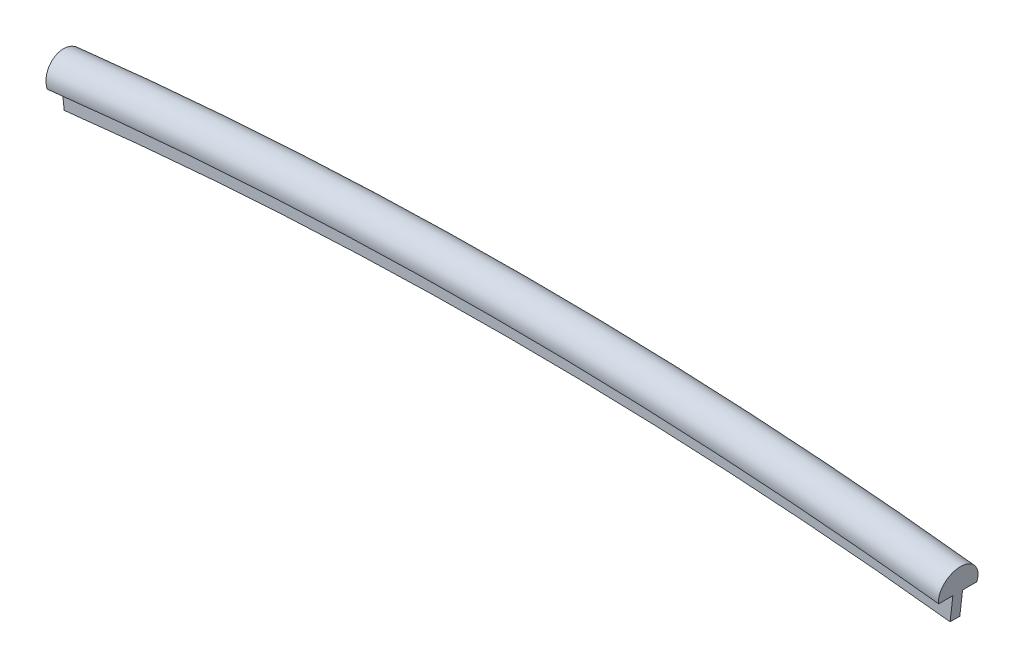
SolidWorks part; units mm, degrees
ref_plane "Front Plane" through (0, 0, 0) normal (0, 0, 1) x (1, 0, 0)
ref_plane "Top Plane" through (0, 0, 0) normal (0, 1, 0) x (1, 0, 0)
ref_plane "Right Plane" through (0, 0, 0) normal (1, 0, 0) x (0, 0, -1)
sketch "Sketch2" plane through (0, 0, 0) normal (1, 0, 0) x (0, 0, -1)
  line L0 (0, 241.3) -> (0, 0) construction
  line L2 (0, 241.3) -> (0, 239.8) construction
  line L3 (0, 239.8) -> (0.3, 239.8)
  line L4 (0, 239.8) -> (-0.3, 239.8)
  line L5 (-0.3, 239.8) -> (-0.3, 241.3)
  line L6 (0.3, 239.8) -> (0.3, 241.3)
  line L7 (0, 241.3) -> (0, 242.8) construction
  line L8 (-1.18, 241.3) -> (-0.3, 241.3)
  line L9 (0.3, 241.3) -> (1.18, 241.3)
  arc A0 (-1.18, 241.3) -> (1.18, 241.3) centre (0, 241.586) cw
  point P14 (0, 241.3)
ref_axis "Axis2" through (0, 0, 70.5976) along (0, 0, -1)
revolve "Revolve1" add sketch "Sketch2" angle 6.563 about axis through (0, 0, 70.5976) along (0, 0, -1)
